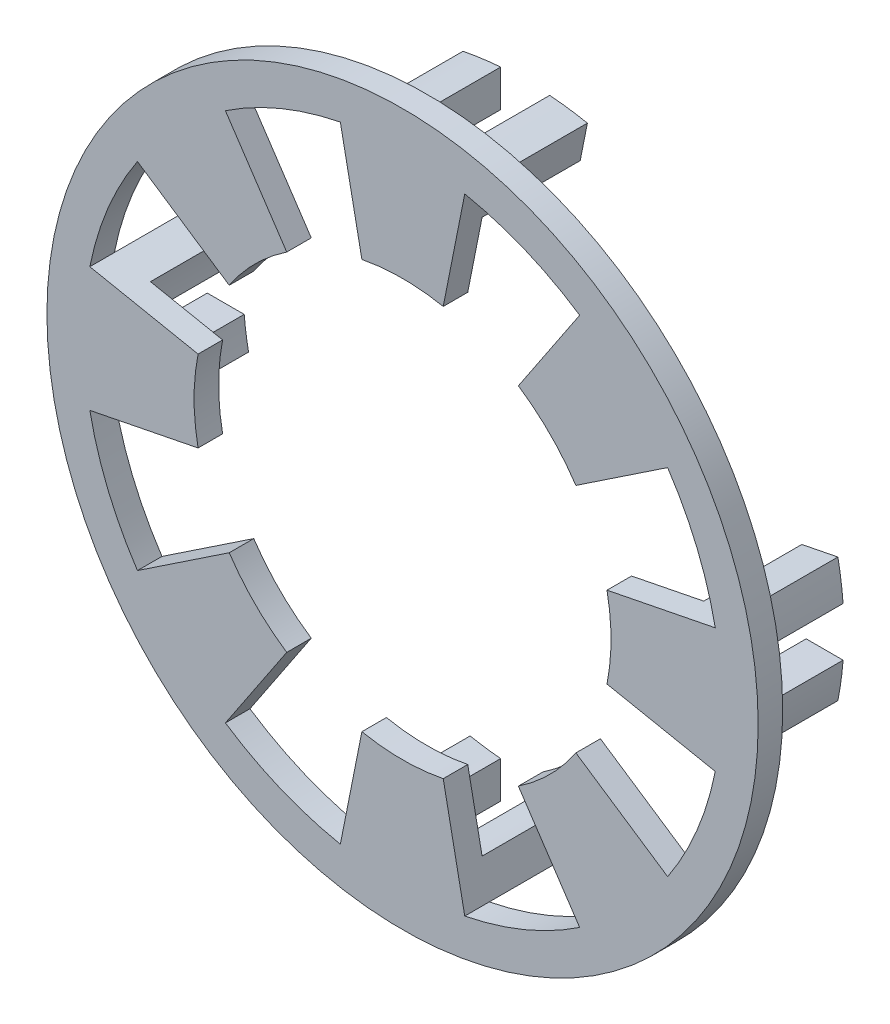
SolidWorks part; units mm, degrees
ref_plane "Front Plane" through (0, 0, 0) normal (0, 0, 1) x (1, 0, 0)
ref_plane "Top Plane" through (0, 0, 0) normal (0, 1, 0) x (1, 0, 0)
ref_plane "Right Plane" through (0, 0, 0) normal (1, 0, 0) x (0, 0, -1)
sketch "Sketch1" plane through (0, 0, 0) normal (0, 0, 1) x (1, 0, 0)
  line L0 (0, 0) -> (0, 23.0788) construction
  line L1 (2.5362, 12.7502) -> (1.6583, 8.3367)
  line L2 (-2.5362, 12.7502) -> (-1.6583, 8.3367)
  line L3 (10.8091, 7.2224) -> (7.0675, 4.7223)
  line L4 (7.2224, 10.8091) -> (4.7223, 7.0675)
  line L5 (12.7502, -2.5362) -> (8.3367, -1.6583)
  line L6 (12.7502, 2.5362) -> (8.3367, 1.6583)
  line L7 (7.2224, -10.8091) -> (4.7223, -7.0675)
  line L8 (10.8091, -7.2224) -> (7.0675, -4.7223)
  line L9 (-2.5362, -12.7502) -> (-1.6583, -8.3367)
  line L10 (2.5362, -12.7502) -> (1.6583, -8.3367)
  line L11 (-10.8091, -7.2224) -> (-7.0675, -4.7223)
  line L12 (-7.2224, -10.8091) -> (-4.7223, -7.0675)
  line L13 (-12.7502, 2.5362) -> (-8.3367, 1.6583)
  line L14 (-12.7502, -2.5362) -> (-8.3367, -1.6583)
  line L15 (-7.2224, 10.8091) -> (-4.7223, 7.0675)
  line L16 (-10.8091, 7.2224) -> (-7.0675, 4.7223)
  line L18 (-6, -5) -> (6, -5) construction
  line L19 (-6, -5) -> (-6, 5) construction
  line L20 (-6, 5) -> (6, 5) construction
  line L21 (6, -5) -> (6, 5) construction
  line L22 (-6, -5) -> (6, 5) construction
  line L23 (-6, 5) -> (6, -5) construction
  circle A0 centre (0, 0) radius 14.5
  circle A1 centre (0, 0) radius 13
  circle A2 centre (0, 0) radius 8.5
  point P41 (0, 0)
  dimension "D1" = 29
  dimension "D2" = 26
  dimension "D3" = 17
  dimension "D4" = 11.25
  dimension "D5" = 11.25
  dimension "D7" = 10
  dimension "D8" = 12
  dimension "D6" = 8
extrude "Boss-Extrude1" add sketch "Sketch1" along normal blind 1 contours A2 L0 A1 L2 | A2 L3 A1 L4 | A2 L5 A1 L6 | A2 L7 A1 L8 | A2 L9 A1 L10 | A2 L11 A1 L12 | A2 L13 A1 L14 | A2 L15 A1 L16 | A0 A1 L15
ref_plane "Plane1" through (0, 0, -5) normal (0, 0, 1) x (1, 0, 0)
sketch "Sketch2" plane through (0, 0, 0) normal (0, 0, -1) x (-1, 0, 0)
  line L0 (0, 0) -> (0, 17.7378) construction
  line L1 (1.2681, 6.3751) -> (2.5362, 12.7502)
  line L2 (-1.2681, 6.3751) -> (-2.5362, 12.7502)
  line L3 (6.3751, -1.2681) -> (12.7502, -2.5362)
  line L4 (1, 6.4226) -> (1, 12.9615)
  line L5 (6.3751, 1.2681) -> (12.7502, 2.5362)
  line L6 (-1, 12.9615) -> (-1, 6.4226)
  line L7 (6.4226, -1) -> (12.9615, -1)
  line L8 (12.9615, 1) -> (6.4226, 1)
  line L9 (-1.2681, -6.3751) -> (-2.5362, -12.7502)
  line L10 (1.2681, -6.3751) -> (2.5362, -12.7502)
  line L11 (-1, -6.4226) -> (-1, -12.9615)
  line L12 (1, -12.9615) -> (1, -6.4226)
  line L13 (-6.3751, 1.2681) -> (-12.7502, 2.5362)
  line L14 (-6.3751, -1.2681) -> (-12.7502, -2.5362)
  line L15 (-6.4226, 1) -> (-12.9615, 1)
  line L16 (-12.9615, -1) -> (-6.4226, -1)
  circle A0 centre (0, 0) radius 14.5
  arc A1 (1.2681, 6.3751) -> (-1.2681, 6.3751) centre (0, 0) ccw
  circle A2 centre (0, 0) radius 13
  arc A3 (6.3751, -1.2681) -> (6.3751, 1.2681) centre (0, 0) ccw
  circle A4 centre (0, 0) radius 11.5
  arc A5 (-1.2681, -6.3751) -> (1.2681, -6.3751) centre (0, 0) ccw
  arc A7 (-6.3751, 1.2681) -> (-6.3751, -1.2681) centre (0, 0) ccw
  point P39 (0, 0)
  line M12 (-2.5362, 12.7502) -> (-1.6583, 8.3367)
  line M20 (12.7502, 2.5362) -> (8.3367, 1.6583)
  line M28 (2.5362, -12.7502) -> (1.6583, -8.3367)
  line M36 (-12.7502, -2.5362) -> (-8.3367, -1.6583)
  dimension "D1" = 29
  dimension "D4" = 13
  dimension "D7" = 26
  dimension "D9" = 23
  dimension "D2" = 11.25
  dimension "D3" = 11.25
  dimension "D5" = 1
  dimension "D6" = 1
  dimension "D8" = 4
extrude "Boss-Extrude2" add sketch "Sketch2" along normal blind 4 contours A4 L12 A2 M28 | A4 L9 A2 L11 | A4 L3 A2 L7 | A4 L8 A2 M20 | A4 L1 A2 L4 | A4 L6 A2 M12 | A4 L13 A2 L15 | A4 L16 A2 M36
sketch "Sketch3" plane through (0, 0, 0) normal (0, 0, -1) x (-1, 0, 0)
  circle A0 centre (0, 0) radius 13
  circle A1 centre (0, 0) radius 14.5
  dimension "D1" = 26
  dimension "D2" = 29
extrude "Boss-Extrude3" [suppressed] add sketch "Sketch3" along normal blind 10
